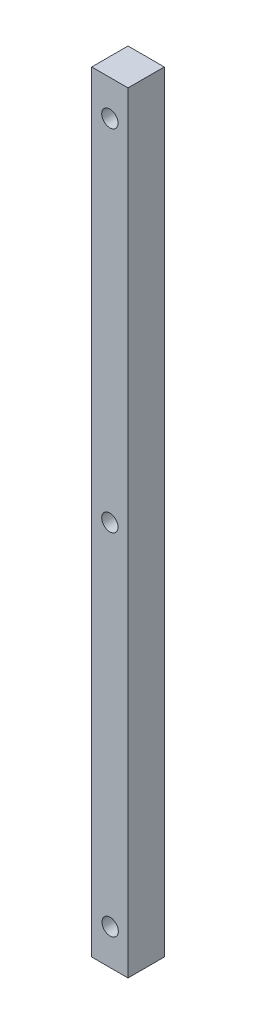
SolidWorks part; units mm, degrees
material "7075-T6, Plate (SS)"
ref_plane "Front Plane" through (0, 0, 0) normal (0, 0, 1) x (1, 0, 0)
ref_plane "Top Plane" through (0, 0, 0) normal (0, 1, 0) x (1, 0, 0)
ref_plane "Right Plane" through (0, 0, 0) normal (1, 0, 0) x (0, 0, -1)
sketch "Sketch1" plane through (0, 0, 0) normal (0, 0, 1) x (1, 0, 0)
  line L1 (-2.5794, 6.2614) -> (2.5006, 6.2614)
  line L2 (-2.5794, 6.2614) -> (-2.5794, -101.6886)
  line L3 (-2.5794, -101.6886) -> (2.5006, -101.6886)
  line L4 (2.5006, 6.2614) -> (2.5006, -101.6886)
  dimension "D1" = 5.08
  dimension "D2" = 107.95
extrude "Boss-Extrude1" add sketch "Sketch1" along normal blind 5.08
sketch "Sketch3" plane through (0, 0, 5.08) normal (0, 0, 1) x (1, 0, 0)
  line L0 (-0.0394, 6.2614) -> (-0.0394, -101.6886) construction
  line L1 (2.5006, 6.2614) -> (-2.5794, 6.2614) construction
  line L2 (-2.5794, -101.6886) -> (2.5006, -101.6886) construction
  circle A1 centre (-0.0394, -47.7136) radius 1.143
  circle A2 centre (-0.0394, 1.2864) radius 1.143
  circle A3 centre (0, -96.7136) radius 1.143
  point P13 (-0.0394, -47.7136)
  dimension "D1" = 2.286
  dimension "D2" = 49
  dimension "D3" = 2.286
  dimension "D4" = 49
  dimension "D5" = 2.286
extrude "Cut-Extrude1" cut sketch "Sketch3" against normal up to next
